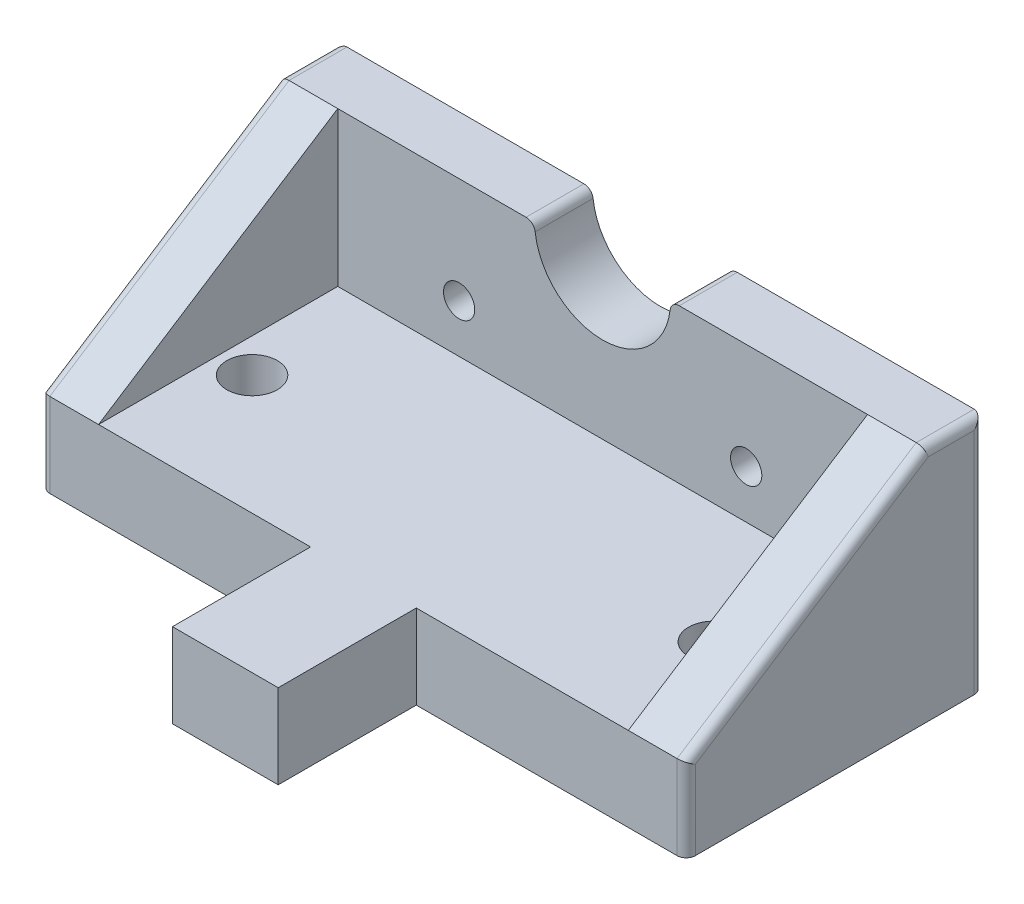
SolidWorks part; units mm, degrees
ref_plane "Front Plane" through (0, 0, 0) normal (0, 0, 1) x (1, 0, 0)
ref_plane "Top Plane" through (0, 0, 0) normal (0, 1, 0) x (1, 0, 0)
ref_plane "Right Plane" through (0, 0, 0) normal (1, 0, 0) x (0, 0, -1)
sketch "Sketch1" plane through (0, 0, 0) normal (0, 0, 1) x (1, 0, 0)
  line L1 (-35.11, -12.95) -> (35.11, -12.95)
  line L2 (-35.11, -12.95) -> (-35.11, 12.95)
  line L3 (-35.11, 12.95) -> (35.11, 12.95)
  line L4 (35.11, -12.95) -> (35.11, 12.95)
  line L5 (-35.11, -12.95) -> (35.11, 12.95) construction
  line L6 (-35.11, 12.95) -> (35.11, -12.95) construction
  point P0 (0, 0)
  dimension "D1" = 70.22
  dimension "D2" = 25.9
extrude "Boss-Extrude1" add sketch "Sketch1" against normal blind 47.34
sketch "Sketch6" plane through (0, 12.95, 0) normal (0, 1, 0) x (1, 0, 0)
  line L1 (-5.75, 15.02) -> (-35.11, 15.02)
  line L2 (-5.75, 15.02) -> (-5.75, 0)
  line L3 (-5.75, 0) -> (-35.11, 0)
  line L4 (-35.11, 15.02) -> (-35.11, 0)
extrude "Cut-Extrude1" cut sketch "Sketch6" against normal through all
mirror "Mirror1" about plane through (0, 0, 0) normal (1, 0, 0) of "Cut-Extrude1"
sketch "Sketch8" plane through (0, 12.95, 0) normal (0, 1, 0) x (1, 0, 0)
  line L0 (35.11, 41.04) -> (-35.11, 41.04) construction
  line L1 (-28.81, 0) -> (28.81, 0)
  line L2 (-28.81, 0) -> (-28.81, 41.04)
  line L3 (-28.81, 41.04) -> (28.81, 41.04)
  line L4 (28.81, 0) -> (28.81, 41.04)
  line L5 (28.81, 47.34) -> (28.81, 0) construction
extrude "Cut-Extrude2" cut sketch "Sketch8" against normal blind 16.75
sketch "Sketch12" plane through (35.11, 0, 0) normal (1, 0, 0) x (0, 0, -1)
  line L0 (15.02, -3.8) -> (41.04, 12.95)
  line L1 (47.34, 12.95) -> (15.02, 12.95) construction
  line L2 (15.02, 12.95) -> (41.04, 12.95)
  line L3 (15.02, 12.95) -> (15.02, -3.8)
extrude "Cut-Extrude3" cut sketch "Sketch12" against normal through all
sketch "Sketch16" plane through (0, 0, -41.04) normal (0, 0, 1) x (1, 0, 0)
  line L0 (28.81, 12.95) -> (-28.81, 12.95) construction
  arc A0 (-7.3954, 12.95) -> (7.3954, 12.95) centre (0, 12.95) ccw
extrude "Cut-Extrude4" cut sketch "Sketch16" against normal through all and the other way through all
fillet "Fillet9" radius 1 10 edges at (-35.11, -8.375, -15.02) (-35.11, 4.575, -28.03) (-35.11, 12.95, -44.19) (-35.11, 0, -47.34) (-7.3954, 12.95, -44.19) (7.3954, 12.95, -44.19) (35.11, 0, -47.34) (35.11, 12.95, -44.19) (35.11, 4.575, -28.03) (35.11, -8.375, -15.02)
sketch "Sketch18" plane through (0, 0, -47.34) normal (0, 0, -1) x (-1, 0, 0)
  line L1 (-34.11, 12.95) -> (-8.3357, 12.95) construction
  line L2 (-15.61, 12.95) -> (-35.11, 12.95)
  line L3 (-15.61, 12.95) -> (-15.61, 1.45)
  line L4 (-15.61, 1.45) -> (-35.11, 1.45)
  line L8 (-35.11, 12.95) -> (-35.11, 1.45)
  line L9 (-35.11, -12.95) -> (-35.11, 11.95) construction
  line L10 (8.3357, 12.95) -> (34.11, 12.95) construction
  line L11 (15.61, 12.95) -> (35.11, 12.95)
  line L13 (15.61, 12.95) -> (15.61, 1.45)
  line L14 (15.61, 1.45) -> (35.11, 1.45)
  line L15 (35.11, 12.95) -> (35.11, 1.45)
  line L16 (35.11, 11.95) -> (35.11, -12.95) construction
  dimension "D1" = 19.5
  dimension "D2" = 11.5
  dimension "D3" = 19.5
hole_wizard "CBORE for M3 SBHCS1" positions "Sketch20" profile "Sketch19" counterbore size "M3" standard "Ansi Metric" end condition through all
sketch "Sketch20" plane through (0, 0, -47.34) normal (0, 0, -1) x (-1, 0, 0)
  point P1 (-15.61, 1.45)
  point P4 (15.61, 1.45)
sketch "Sketch19" plane through (15.61, 1.45, -47.34) normal (1, 0, 0) x (0, 1, 0)
  line L0 (0, 0) -> (0, 47.34)
  line L1 (0, 47.34) -> (1.7, 47.34)
  line L3 (1.7, 47.34) -> (1.7, 1.65)
  line L4 (1.7, 1.65) -> (3.35, 1.65)
  line L5 (3.35, 1.65) -> (3.35, 0)
  line L7 (3.35, 0) -> (0, 0)
  line L11 (0, -6.35) -> (0, 107.95) construction
  dimension "Thru Hole Dia." = 3.4
  dimension "Thru Hole Depth" = 47.34
  dimension "C'Bore Dia." = 6.7
  dimension "C'Bore Depth" = 1.65
sketch "Sketch21" plane through (0, -12.95, 0) normal (0, -1, 0) x (1, 0, 0)
  line L0 (-5.75, -15.02) -> (-34.11, -15.02) construction
  line L1 (-35.11, -46.34) -> (-35.11, -16.02) construction
  line L2 (-25.11, -15.02) -> (-35.11, -15.02)
  line L3 (-25.11, -15.02) -> (-25.11, -28.02)
  line L4 (-25.11, -28.02) -> (-35.11, -28.02)
  line L5 (-35.11, -15.02) -> (-35.11, -28.02)
  line L6 (5.75, -15.02) -> (34.11, -15.02) construction
  line L7 (25.11, -15.02) -> (35.11, -15.02)
  line L8 (25.11, -15.02) -> (25.11, -28.02)
  line L9 (25.11, -28.02) -> (35.11, -28.02)
  line L10 (35.11, -15.02) -> (35.11, -28.02)
  line L11 (35.11, -46.34) -> (35.11, -16.02) construction
  dimension "D1" = 13
  dimension "D2" = 10
  dimension "D3" = 10
  dimension "D4" = 13
hole_wizard "CBORE for M5 SBHCS1" positions "Sketch23" profile "Sketch22" counterbore size "M5" standard "Ansi Metric" end condition through all
sketch "Sketch23" plane through (0, -12.95, 0) normal (0, -1, 0) x (1, 0, 0)
  point P1 (-25.11, -28.02)
  point P4 (25.11, -28.02)
sketch "Sketch22" plane through (-25.11, -12.95, -28.02) normal (1, 0, 0) x (0, 0, -1)
  line L0 (0, 0) -> (0, 25.9)
  line L1 (0, 25.9) -> (2.75, 25.9)
  line L3 (2.75, 25.9) -> (2.75, 2.75)
  line L4 (2.75, 2.75) -> (5.25, 2.75)
  line L5 (5.25, 2.75) -> (5.25, 0)
  line L7 (5.25, 0) -> (0, 0)
  line L11 (0, -6.35) -> (0, 107.95) construction
  dimension "Thru Hole Dia." = 5.5
  dimension "Thru Hole Depth" = 25.9
  dimension "C'Bore Dia." = 10.5
  dimension "C'Bore Depth" = 2.75
